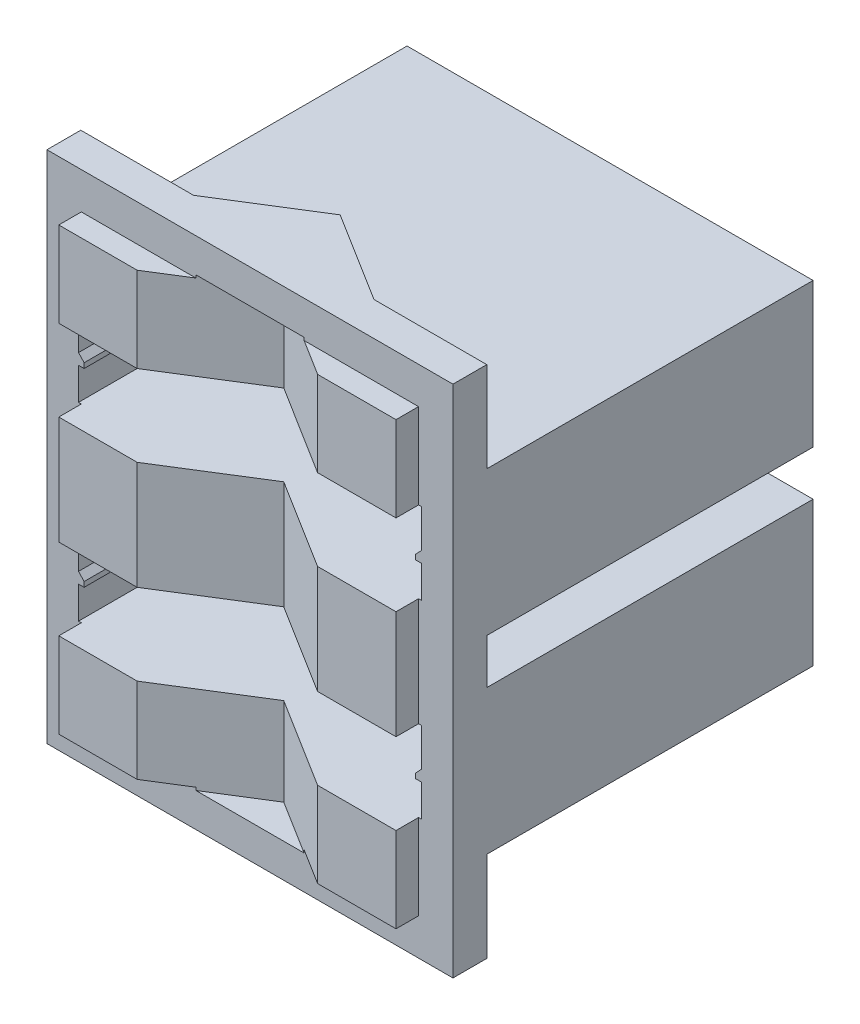
SolidWorks part; units mm, degrees
ref_plane "Front Plane" through (0, 0, 0) normal (0, 0, 1) x (1, 0, 0)
ref_plane "Top Plane" through (0, 0, 0) normal (0, 1, 0) x (1, 0, 0)
ref_plane "Right Plane" through (0, 0, 0) normal (1, 0, 0) x (0, 0, -1)
sketch "Sketch1" plane through (0, 0, 0) normal (0, 0, 1) x (1, 0, 0)
  line L0 (0, 0) -> (0, 39.6006)
  line L1 (0, 0) -> (36, 0)
  line L2 (36, 0) -> (36, 39.6006)
  line L3 (0, 39.6006) -> (36, 39.6006)
  dimension "D1" = 39.6006
  dimension "D2" = 36
extrude "Boss-Extrude1" add sketch "Sketch1" against normal blind 33.93
sketch "Sketch2" plane through (36, 0, 0) normal (1, 0, 0) x (0, 0, -1)
  line L0 (33.93, 39.6006) -> (0, 39.6006) construction
  line L1 (5, 39.6006) -> (33.93, 39.6006)
  line L2 (5, 39.6006) -> (5, 34.6006)
  line L3 (5, 34.6006) -> (33.93, 34.6006)
  line L4 (33.93, 39.6006) -> (33.93, 34.6006)
  line L5 (33.93, 0) -> (33.93, 39.6006) construction
  line L6 (0, 0) -> (0, 39.6006) construction
  line L7 (33.93, 21.8003) -> (5, 21.8003)
  line L8 (33.93, 21.8003) -> (33.93, 17.8003)
  line L9 (33.93, 17.8003) -> (5, 17.8003)
  line L10 (5, 21.8003) -> (5, 17.8003)
  line L11 (33.93, 0) -> (5, 0)
  line L12 (33.93, 0) -> (33.93, 5)
  line L13 (33.93, 5) -> (5, 5)
  line L14 (5, 0) -> (5, 5)
  line L15 (5, 19.8003) -> (0, 19.8003) construction
  dimension "D1" = 5
  dimension "D2" = 5
  dimension "D3" = 4
  dimension "D4" = 5
extrude "Cut-Extrude1" cut sketch "Sketch2" against normal through all
sketch "Sketch3" plane through (0, 0, 0) normal (0, 0, 1) x (1, 0, 0)
  line L0 (36, 39.6006) -> (0, 39.6006) construction
  line L1 (10, 39.6006) -> (26, 39.6006)
  line L2 (10, 39.6006) -> (10, 34.6006)
  line L3 (10, 34.6006) -> (26, 34.6006)
  line L4 (26, 39.6006) -> (26, 34.6006)
  line L5 (0, 0) -> (36, 0) construction
  line L6 (10, 21.8003) -> (26, 21.8003)
  line L7 (10, 21.8003) -> (10, 17.8003)
  line L8 (10, 17.8003) -> (26, 17.8003)
  line L9 (26, 21.8003) -> (26, 17.8003)
  line L10 (10, 0) -> (26, 0)
  line L11 (10, 0) -> (10, 5)
  line L12 (10, 5) -> (26, 5)
  line L13 (26, 0) -> (26, 5)
  line L14 (18, 34.6006) -> (18, 21.8003) construction
  line L15 (18, 17.8003) -> (18, 5) construction
  point P6 (18, 39.6006)
  point P8 (18, 39.6006)
  dimension "D1" = 5
  dimension "D2" = 16
  dimension "D3" = 4
extrude "Cut-Extrude2" cut sketch "Sketch3" against normal through all
sketch "Sketch4" plane through (0, 34.6006, 0) normal (0, 1, 0) x (1, 0, 0)
  line L0 (10, 0) -> (18, 5)
  line L1 (10, 0) -> (26, 0) construction
  line L2 (18, 5) -> (26, 0)
  line L3 (36, 0) -> (26, 0) construction
  line L4 (10, 0) -> (26, 0)
  dimension "D2" = 5
extrude "Cut-Extrude3" cut sketch "Sketch4" against normal through all
sketch "Sketch5" plane through (0, 0, 0) normal (0, 0, 1) x (1, 0, 0)
  line L0 (2.8, 15) -> (33.2, 15)
  line L1 (2.8, 31.8006) -> (33.2, 31.8006)
  line L2 (2.8, 31.8006) -> (2.8, 24.6006)
  line L3 (2.8, 24.6006) -> (33.2, 24.6006)
  line L4 (33.2, 31.8006) -> (33.2, 24.6006)
  line L5 (2.8, 15) -> (2.8, 7.8)
  line L6 (2.8, 7.8) -> (33.2, 7.8)
  line L7 (33.2, 15) -> (33.2, 7.8)
  line L8 (18, 31.8006) -> (18, 34.6006) construction
  line L9 (18, 15) -> (18, 24.6006) construction
  line L10 (10, 39.6006) -> (0, 39.6006) construction
  line L11 (0, 0) -> (10, 0) construction
  dimension "D1" = 30.4
  dimension "D2" = 7.2
  dimension "D3" = 7.8
  dimension "D4" = 7.8
extrude "Cut-Extrude4" cut sketch "Sketch5" against normal blind 30.93
sketch "Sketch6" plane through (0, 0, -30.93) normal (0, 0, 1) x (1, 0, 0)
  line L0 (18, 29.6606) -> (18, 31.8006) construction
  line L1 (15.11, 29.6606) -> (20.89, 29.6606)
  line L3 (15.11, 26.5006) -> (20.89, 26.5006)
  line L5 (15.11, 12.86) -> (20.89, 12.86)
  line L7 (15.11, 9.7) -> (20.89, 9.7)
  line L9 (18, 26.5006) -> (18, 12.86) construction
  line L10 (22.47, 28.2006) -> (33.2, 28.2006) construction
  line L11 (2.8, 24.6006) -> (33.2, 24.6006) construction
  line L12 (33.2, 24.6006) -> (33.2, 31.8006) construction
  line L13 (22.47, 11.4) -> (33.2, 11.4) construction
  line L14 (33.2, 7.8) -> (33.2, 15) construction
  line L16 (18, 7.8) -> (10, 7.8) construction
  arc A0 (15.11, 29.6606) -> (15.11, 26.5006) centre (15.11, 28.0806) ccw
  arc A1 (20.89, 29.6606) -> (20.89, 26.5006) centre (20.89, 28.0806) cw
  arc A2 (15.11, 12.86) -> (15.11, 9.7) centre (15.11, 11.28) ccw
  arc A3 (20.89, 12.86) -> (20.89, 9.7) centre (20.89, 11.28) cw
  point P25 (13.53, 28.0806)
  point P26 (22.47, 28.0806)
  dimension "D1" = 3.16
  dimension "D2" = 8.94
  dimension "D3" = 1.9
  dimension "D4" = 1.9
extrude "Cut-Extrude5" cut sketch "Sketch6" against normal through all
sketch "Sketch7" plane through (0, 0, 0) normal (0, 0, 1) x (1, 0, 0)
  line L4 (2.8, 31.8006) -> (2.8, 24.6006) construction
  line L5 (2.8, 28.5229) -> (3.61, 27.6706) construction
  line L6 (3.61, 27.6706) -> (3.61, 27.3506) construction
  line L7 (3.61, 27.3506) -> (2.8, 27.3506) construction
  line L8 (2.8, 27.3506) -> (2.8, 28.5229) construction
  line L9 (2.8, 24.6006) -> (10, 24.6006) construction
  line L10 (2.8, 28.4229) -> (2.8, 27.4506)
  line L11 (2.8, 27.4506) -> (3.3, 27.4506)
  line L12 (3.3, 27.4506) -> (3.3, 27.8968)
  line L13 (3.3, 27.8968) -> (2.8, 28.4229)
  line L14 (2.8, 15) -> (2.8, 7.8) construction
  line L15 (2.8, 7.8) -> (10, 7.8) construction
  line L16 (2.8, 15) -> (2.8, 7.8) construction
  line B0 (2.8, 11.7224) -> (3.61, 10.87) construction
  line B1 (3.61, 10.87) -> (3.61, 10.55) construction
  line B2 (3.61, 10.55) -> (2.8, 10.55) construction
  line B3 (2.8, 10.55) -> (2.8, 11.7224) construction
  line B4 (2.8, 11.6224) -> (2.8, 10.65)
  line B5 (2.8, 10.65) -> (3.3, 10.65)
  line B6 (3.3, 10.65) -> (3.3, 11.0962)
  line B7 (3.3, 11.0962) -> (2.8, 11.6224)
  dimension "D1" = 0.81
  dimension "D2" = 1.1724
  dimension "D3" = 0.32
  dimension "D4" = 43.54
  dimension "D5" = 2.75
  dimension "D6" = 0.1
  dimension "D7" = 0.1
  dimension "D8" = 0.5
  dimension "D9" = 2.75
sketch_block_instance "Block3-1"
sketch_block "Block3" parameters "D1"=0.81, "D2"=1.1724, "D3"=0.32, "D4"=43.54, "D5"=0.1, "D6"=0.1, "D7"=0.5
extrude "Boss-Extrude2" add sketch "Sketch7" against normal up to next
ref_plane "Plane1" through (18, 0, 0) normal (1, 0, 0) x (0, 0, -1)
mirror "Mirror1" about plane through (18, 0, 0) normal (1, 0, 0) of "Boss-Extrude2"
sketch "Sketch8" plane through (0, 34.6006, 0) normal (0, 1, 0) x (1, 0, 0)
  line L0 (10, 5) -> (18, 10)
  line L1 (18, 10) -> (26, 5)
  line L2 (18, 5) -> (10, 0) construction
  line L3 (10, 5) -> (10, 0)
  line L4 (10, 0) -> (18, 5)
  line L5 (18, 5) -> (26, 0)
  line L6 (26, 0) -> (26, 5)
extrude "Boss-Extrude3" add sketch "Sketch8" along normal up to surface (5 mm away) up to face at (5, 39.6006, -2.5)
sketch "Sketch9" plane through (0, 17.8003, 0) normal (0, 1, 0) x (1, 0, 0)
  line L0 (10, 5) -> (18, 10)
  line L1 (18, 10) -> (26, 5)
  line L2 (10, 5) -> (10, 0)
  line L3 (10, 0) -> (18, 5)
  line L4 (18, 5) -> (26, 0)
  line L5 (26, 0) -> (26, 5)
  line L6 (10, 0) -> (18, 5) construction
  line L7 (18, 5) -> (26, 0) construction
  line L9 (10, 5) -> (10, 0) construction
extrude "Boss-Extrude4" add sketch "Sketch9" along normal up to next
sketch "Sketch10" plane through (0, 5, 0) normal (0, -1, 0) x (1, 0, 0)
  line L6 (10, 0) -> (18, -5)
  line L7 (18, -5) -> (26, 0)
  line L8 (26, 0) -> (26, -5)
  line L9 (26, -5) -> (18, -10)
  line L10 (18, -10) -> (10, -5)
  line L11 (10, -5) -> (10, 0)
extrude "Boss-Extrude5" add sketch "Sketch10" along normal up to surface (5 mm away) up to face at (5, 0, -2.5)
sketch "Sketch11" plane through (0, 39.6006, 0) normal (0, 1, 0) x (1, 0, 0)
  line L1 (0, 5) -> (10, 5)
  line L2 (0, 5) -> (0, 0)
  line L3 (0, 0) -> (36, 0)
  line L4 (36, 5) -> (36, 0)
  line L8 (26, 5) -> (36, 5)
  line L9 (10, 5) -> (18, 10)
  line L10 (18, 10) -> (26, 5)
extrude "Boss-Extrude6" add sketch "Sketch11" along normal blind 3
ref_plane "Plane2" through (0, 19.8003, 0) normal (0, 1, 0) x (1, 0, 0)
mirror "Mirror2" about plane through (0, 19.8003, 0) normal (0, 1, 0) of "Boss-Extrude6"
sketch "Sketch12" plane through (0, 0, 0) normal (0, 0, 1) x (1, 0, 0)
  line L0 (18, 39.6003) -> (18, 42.6006) construction
  line L1 (2.8, 39.6003) -> (33.2, 39.6003)
  line L2 (2.8, 39.6003) -> (2.8, 28.4229)
  line L3 (2.8, 0.0003) -> (33.2, 0.0003)
  line L4 (33.2, 39.6003) -> (33.2, 28.4229)
  line L5 (3, 19.8003) -> (0, 19.8003) construction
  line L6 (0, 42.6006) -> (0, -3) construction
  line L7 (2.8, 27.4506) -> (3.3, 27.4506) construction
  line L8 (0, 42.6006) -> (36, 42.6006)
  line L9 (0, 42.6006) -> (0, -3)
  line L10 (0, -3) -> (36, -3)
  line L11 (36, 42.6006) -> (36, -3)
  line L12 (3.3, 27.4506) -> (3.3, 27.8968) construction
  line L13 (3.3, 27.8968) -> (2.8, 28.4229) construction
  line L14 (2.8, 27.4506) -> (3.3, 27.4506)
  line L15 (3.3, 27.4506) -> (3.3, 27.8968)
  line L16 (3.3, 27.8968) -> (2.8, 28.4229)
  line L17 (33.2, 27.4506) -> (32.7, 27.4506) construction
  line L18 (32.7, 27.4506) -> (32.7, 27.8968) construction
  line L19 (32.7, 27.8968) -> (33.2, 28.4229) construction
  line L20 (33.2, 27.4506) -> (32.7, 27.4506)
  line L21 (32.7, 27.4506) -> (32.7, 27.8968)
  line L22 (32.7, 27.8968) -> (33.2, 28.4229)
  line L23 (33.2, 10.65) -> (32.7, 10.65) construction
  line L24 (32.7, 10.65) -> (32.7, 11.0962) construction
  line L25 (32.7, 11.0962) -> (33.2, 11.6224) construction
  line L26 (33.2, 10.65) -> (32.7, 10.65)
  line L27 (32.7, 10.65) -> (32.7, 11.0962)
  line L28 (32.7, 11.0962) -> (33.2, 11.6224)
  line L29 (2.8, 10.65) -> (3.3, 10.65) construction
  line L30 (3.3, 10.65) -> (3.3, 11.0962) construction
  line L31 (3.3, 11.0962) -> (2.8, 11.6224) construction
  line L32 (2.8, 10.65) -> (3.3, 10.65)
  line L33 (3.3, 10.65) -> (3.3, 11.0962)
  line L34 (3.3, 11.0962) -> (2.8, 11.6224)
  line L35 (2.8, 27.4506) -> (2.8, 11.6224)
  line L36 (2.8, 10.65) -> (2.8, 0.0003)
  line L37 (33.2, 27.4506) -> (33.2, 11.6224)
  line L38 (33.2, 10.65) -> (33.2, 0.0003)
  line L39 (18, 0.0003) -> (18, -3) construction
  dimension "D2" = 39.6
extrude "Cut-Extrude6" cut sketch "Sketch12" against normal blind 2
sketch "Sketch13" plane through (0, 0, 0) normal (0, 0, 1) x (1, 0, 0)
  line L0 (3.05, 39.3503) -> (32.95, 39.3503)
  line L1 (2.8, 39.6003) -> (33.2, 39.6003)
  line L2 (2.8, 39.6003) -> (2.8, 0.0003)
  line L3 (2.8, 0.0003) -> (33.2, 0.0003)
  line L4 (33.2, 39.6003) -> (33.2, 0.0003)
  line L5 (32.95, 39.3503) -> (32.95, 0.2503)
  line L6 (3.05, 0.2503) -> (32.95, 0.2503)
  line L7 (3.05, 39.3503) -> (3.05, 0.2503)
  dimension "D1" = 0.25
extrude "Cut-Extrude7" cut sketch "Sketch13" against normal up to surface (2 mm away) up to face at (18, 19.8003, -2)
